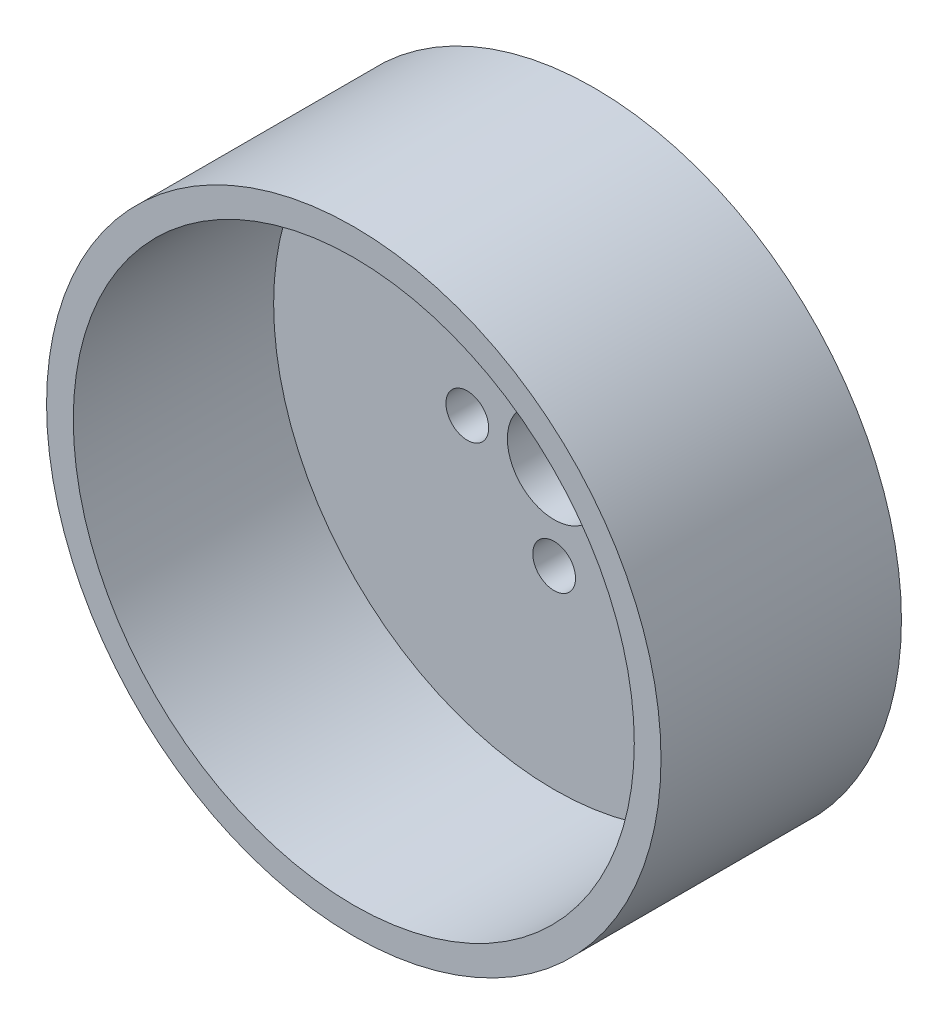
SolidWorks part; units mm, degrees
material "6061 合金"
ref_plane "前视基准面" through (0, 0, 0) normal (0, 0, 1) x (1, 0, 0)
ref_plane "上视基准面" through (0, 0, 0) normal (0, 1, 0) x (1, 0, 0)
ref_plane "右视基准面" through (0, 0, 0) normal (1, 0, 0) x (0, 0, -1)
sketch "草图1" plane through (0, 0, 0) normal (0, 1, 0) x (1, 0, 0)
  line L0 (0, 0) -> (0, -15.6625) construction
  line L1 (-3.5, 0) -> (-23, 0)
  line L2 (-23, 0) -> (-23, -18)
  line L3 (-23, -18) -> (-21, -18)
  line L4 (-21, -18) -> (-21, -3)
  line L5 (-21, -3) -> (-3.5, -3)
  line L6 (-3.5, -3) -> (-3.5, 0)
  dimension "D1" = 7
  dimension "D2" = 42
  dimension "D3" = 3
  dimension "D4" = 2
  dimension "D5" = 18
revolve "旋转1" add sketch "草图1" angle 360 about L0
sketch "草图2" plane through (0, 0, 0) normal (0, 0, -1) x (-1, 0, 0)
  circle A0 centre (0, 0) radius 6.5 construction
  circle A1 centre (6.5, 0) radius 1.6
  circle A2 centre (0, -6.5) radius 1.6
  circle A3 centre (-6.5, 0) radius 1.6
  circle A4 centre (0, 6.5) radius 1.6
  point P14 (0, 0)
  dimension "D1" = 13
  dimension "D2" = 3.2
  dimension "D3" = 4
extrude "切除-拉伸1" cut sketch "草图2" against normal blind 10
